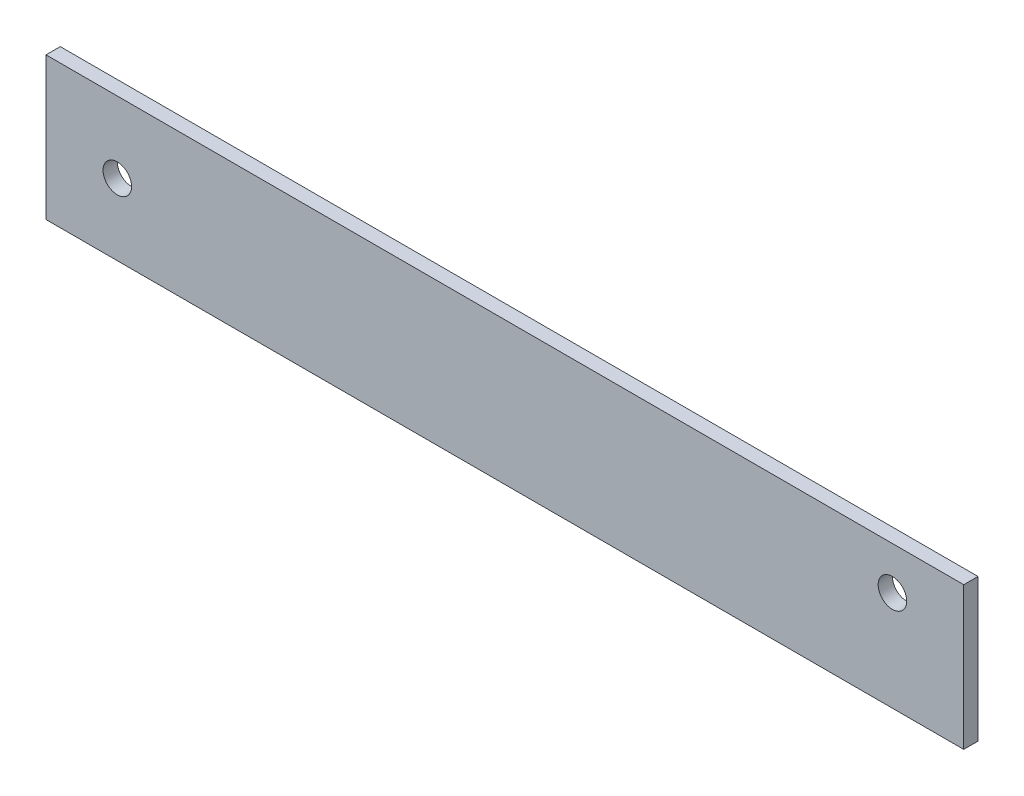
SolidWorks part; units mm, degrees
ref_plane "Plan de face" through (0, 0, 0) normal (0, 0, 1) x (1, 0, 0)
ref_plane "Plan de dessus" through (0, 0, 0) normal (0, 1, 0) x (1, 0, 0)
ref_plane "Plan de droite" through (0, 0, 0) normal (1, 0, 0) x (0, 0, -1)
sketch "Esquisse1" plane through (0, 0, 0) normal (0, 0, 1) x (1, 0, 0)
  line L1 (-35.711, 11.6732) -> (60.789, 11.6732)
  line L2 (-35.711, 11.6732) -> (-35.711, -3.3268)
  line L3 (-35.711, -3.3268) -> (60.789, -3.3268)
  line L4 (60.789, 11.6732) -> (60.789, -3.3268)
  circle A0 centre (-28.211, 4.1732) radius 1.5
  circle A1 centre (53.289, 7.1732) radius 1.5
  dimension "D3" = 7.5
  dimension "D1" = 15
  dimension "D2" = 96.5
  dimension "D4" = 7.5
  dimension "D5" = 7.5
  dimension "D6" = 4.5
extrude "Extrusion1" add sketch "Esquisse1" along normal blind 1.5
